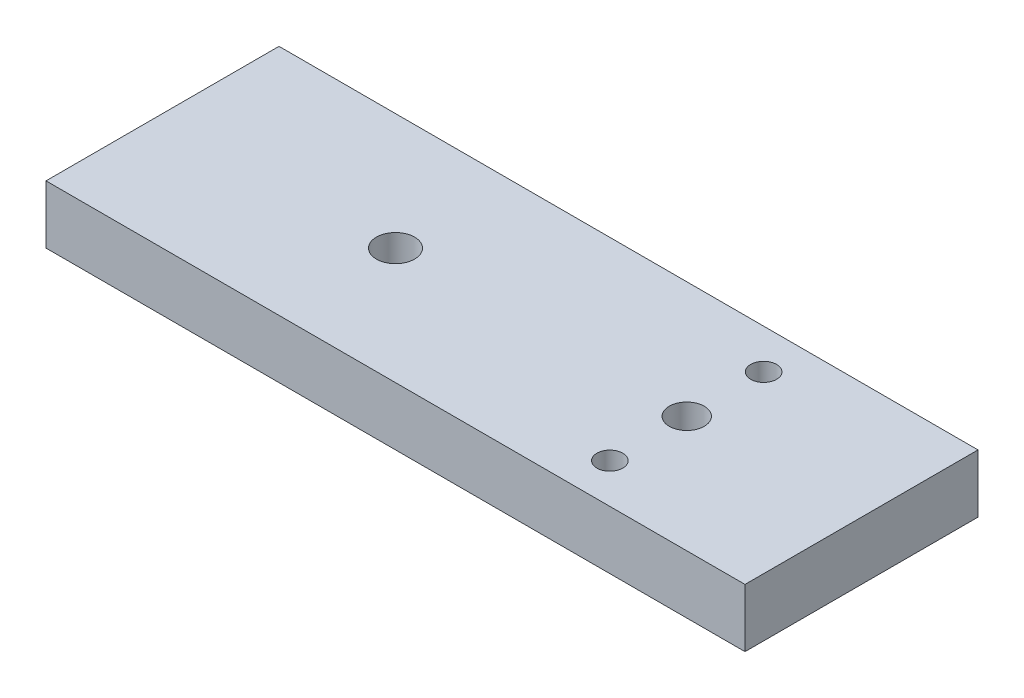
SolidWorks part; units mm, degrees
ref_plane "Front Plane" through (0, 0, 0) normal (0, 0, 1) x (1, 0, 0)
ref_plane "Top Plane" through (0, 0, 0) normal (0, 1, 0) x (1, 0, 0)
ref_plane "Right Plane" through (0, 0, 0) normal (1, 0, 0) x (0, 0, -1)
sketch "Sketch2" plane through (0, 0, 0) normal (0, 1, 0) x (1, 0, 0)
  line L0 (0, 12.7) -> (57.15, 12.7)
  line L1 (0, 0) -> (76.2, 0)
  line L2 (0, 0) -> (0, 25.4)
  line L3 (0, 25.4) -> (76.2, 25.4)
  line L4 (76.2, 0) -> (76.2, 25.4)
  line L5 (57.15, 12.7) -> (57.15, 21.082)
  line L6 (57.15, 12.7) -> (57.15, 4.318)
  circle A0 centre (57.15, 21.082) radius 1.4122
  circle A1 centre (57.15, 4.318) radius 1.4122
  circle A2 centre (57.15, 12.7) radius 1.905
  dimension "D1" = 76.2
  dimension "D2" = 25.4
  dimension "D3" = 57.15
extrude "Boss-Extrude1" add sketch "Sketch2" along normal blind 6.35
sketch "Sketch3" plane through (0, 6.35, 0) normal (0, 1, 0) x (1, 0, 0)
  line L0 (0, 25.4) -> (0, 12.7)
  line L1 (0, 25.4) -> (76.2, 25.4) construction
  line L2 (0, 0) -> (0, 25.4) construction
  line L3 (0, 12.7) -> (25.4, 12.7)
  circle A1 centre (25.4, 12.7) radius 2.0828
extrude "Cut-Extrude1" cut sketch "Sketch3" against normal blind 6.35
